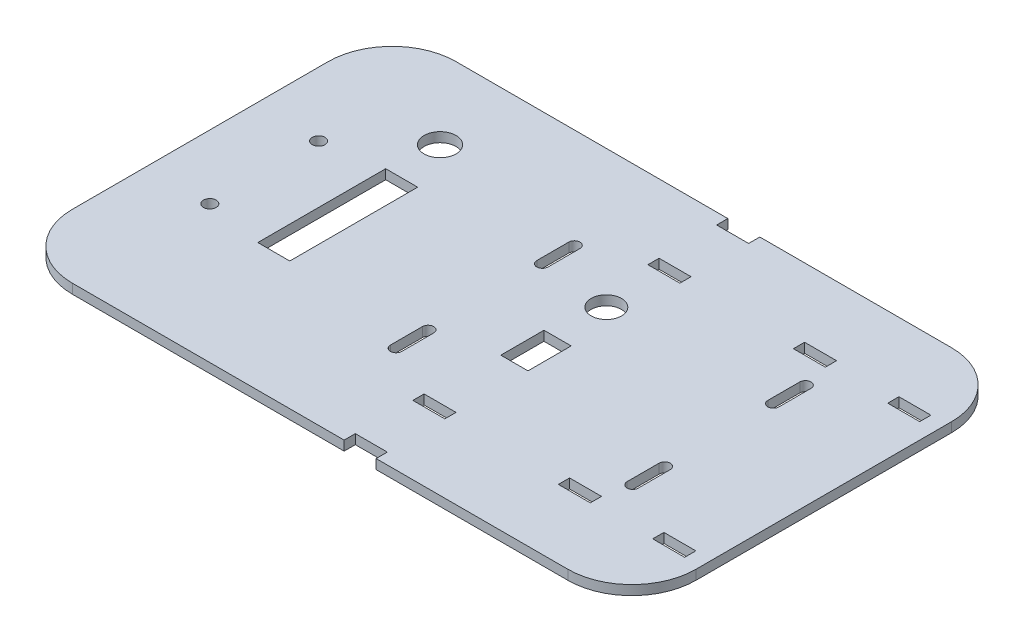
SolidWorks part; units mm, degrees
ref_plane "Plano frontal" through (0, 0, 0) normal (0, 0, 1) x (1, 0, 0)
ref_plane "Plano superior" through (0, 0, 0) normal (0, 1, 0) x (1, 0, 0)
ref_plane "Plano direito" through (0, 0, 0) normal (1, 0, 0) x (0, 0, -1)
sketch "Esboço1" plane through (0, 0, 0) normal (0, 1, 0) x (1, 0, 0)
  line L1 (0, 0) -> (195, 0)
  line L2 (0, 0) -> (0, 120)
  line L3 (0, 120) -> (195, 120)
  line L4 (195, 0) -> (195, 120)
  dimension "D1" = 195
  dimension "D2" = 120
extrude "Ressalto-extrusão1" add sketch "Esboço1" along normal blind 3
fillet "Filete1" radius 20 1 edges at (0, 1.5, 0)
fillet "Filete2" radius 20 1 edges at (195, 1.5, 0)
fillet "Filete3" radius 20 1 edges at (195, 1.5, -120)
fillet "Filete4" radius 20 1 edges at (0, 1.5, -120)
sketch "Esboço2" plane through (0, 3, 0) normal (0, 1, 0) x (1, 0, 0)
  line L0 (195, 20) -> (195, 100) construction
  line L1 (105, 3.5) -> (115, 3.5)
  line L2 (105, 3.5) -> (105, 0)
  line L3 (105, 0) -> (115, 0)
  line L4 (115, 3.5) -> (115, 0)
  line L5 (20, 0) -> (175, 0) construction
  line L6 (175, 120) -> (20, 120) construction
  line L7 (105, 120) -> (115, 120)
  line L8 (105, 120) -> (105, 116.5)
  line L9 (105, 116.5) -> (115, 116.5)
  line L10 (115, 120) -> (115, 116.5)
  line L11 (105, 25) -> (115, 25)
  line L12 (105, 98.5) -> (115, 98.5)
  line L13 (105, 98.5) -> (105, 95)
  line L14 (105, 95) -> (115, 95)
  line L15 (115, 98.5) -> (115, 95)
  line L16 (105, 25) -> (105, 21.5)
  line L17 (105, 21.5) -> (115, 21.5)
  line L18 (115, 25) -> (115, 21.5)
  line L19 (150.5, 25) -> (160.5, 25)
  line L20 (150.5, 25) -> (150.5, 21.5)
  line L21 (150.5, 21.5) -> (160.5, 21.5)
  line L22 (160.5, 25) -> (160.5, 21.5)
  line L23 (180, 25) -> (190, 25)
  line L24 (180, 25) -> (180, 21.5)
  line L25 (180, 21.5) -> (190, 21.5)
  line L26 (190, 25) -> (190, 21.5)
  line L27 (150.5, 98.5) -> (160.5, 98.5)
  line L28 (150.5, 98.5) -> (150.5, 95)
  line L29 (150.5, 95) -> (160.5, 95)
  line L30 (160.5, 98.5) -> (160.5, 95)
  line L31 (180, 98.5) -> (190, 98.5)
  line L32 (180, 98.5) -> (180, 95)
  line L33 (180, 95) -> (190, 95)
  line L34 (190, 98.5) -> (190, 95)
  point P38 (115, 23.25)
  point P39 (190, 23.25)
  dimension "D1" = 10
  dimension "D2" = 3.5
  dimension "D3" = 80
  dimension "D4" = 0
  dimension "D5" = 10
  dimension "D6" = 3.5
  dimension "D7" = 80
  dimension "D8" = 0
  dimension "D9" = 10
  dimension "D10" = 3.5
  dimension "D11" = 21.5
  dimension "D12" = 80
  dimension "D13" = 21.5
  dimension "D14" = 21.5
  dimension "D15" = 21.5
  dimension "D16" = 21.5
  dimension "D17" = 21.5
  dimension "D18" = 80
  dimension "D19" = 10
  dimension "D20" = 3.5
  dimension "D21" = 5
  dimension "D22" = 10
  dimension "D23" = 19.5
  dimension "D24" = 10
  dimension "D25" = 35.5
  dimension "D26" = 3.5
  dimension "D27" = 3.5
  dimension "D28" = 10
  dimension "D29" = 3.5
  dimension "D30" = 5
  dimension "D31" = 10
  dimension "D32" = 3.5
  dimension "D33" = 19.5
  dimension "D34" = 35.5
extrude "Corte-extrusão1" cut sketch "Esboço2" against normal through all
sketch "Esboço3" plane through (0, 3, 0) normal (0, 1, 0) x (1, 0, 0)
  line L0 (162.25, 87) -> (162.25, 77) construction
  line L1 (164, 87) -> (164, 77)
  line L2 (160.5, 87) -> (160.5, 77)
  line L3 (175, 120) -> (115, 120) construction
  line L4 (195, 20) -> (195, 100) construction
  line L5 (162.25, 43) -> (162.25, 33) construction
  line L6 (164, 43) -> (164, 33)
  line L7 (160.5, 43) -> (160.5, 33)
  line L8 (115, 0) -> (175, 0) construction
  line L9 (88.25, 43) -> (88.25, 33) construction
  line L10 (90, 43) -> (90, 33)
  line L11 (86.5, 43) -> (86.5, 33)
  line L12 (88.25, 88.75) -> (88.25, 78.75) construction
  line L13 (90, 88.75) -> (90, 78.75)
  line L14 (86.5, 88.75) -> (86.5, 78.75)
  line L15 (105, 120) -> (20, 120) construction
  line L16 (20, 0) -> (105, 0) construction
  arc A0 (164, 87) -> (160.5, 87) centre (162.25, 87) ccw
  arc A1 (160.5, 77) -> (164, 77) centre (162.25, 77) ccw
  arc A2 (164, 43) -> (160.5, 43) centre (162.25, 43) ccw
  arc A3 (160.5, 33) -> (164, 33) centre (162.25, 33) ccw
  arc A4 (90, 43) -> (86.5, 43) centre (88.25, 43) ccw
  arc A5 (86.5, 33) -> (90, 33) centre (88.25, 33) ccw
  arc A6 (90, 88.75) -> (86.5, 88.75) centre (88.25, 88.75) ccw
  arc A7 (86.5, 78.75) -> (90, 78.75) centre (88.25, 78.75) ccw
  point P2 (162.25, 82)
  point P13 (162.25, 38)
  point P24 (88.25, 38)
  point P31 (88.25, 83.75)
  point P38 (88.25, 77)
  dimension "D1" = 1.75
  dimension "D6" = 1.75
  dimension "D10" = 1.75
  dimension "D14" = 1.75
  dimension "D16" = 43
  dimension "D2" = 10
  dimension "D3" = 33
  dimension "D4" = 32.75
  dimension "D5" = 10
  dimension "D7" = 32.75
  dimension "D8" = 33
  dimension "D9" = 10
  dimension "D11" = 74
  dimension "D12" = 43
  dimension "D13" = 10
  dimension "D15" = 74
extrude "Corte-extrusão2" cut sketch "Esboço3" against normal through all
sketch "Esboço4" plane through (0, 3, 0) normal (0, 1, 0) x (1, 0, 0)
  line L0 (105, 120) -> (20, 120) construction
  line L1 (195, 20) -> (195, 100) construction
  line L2 (20, 0) -> (105, 0) construction
  line L3 (106.5, 61) -> (115, 61)
  line L4 (106.5, 61) -> (106.5, 47.5)
  line L5 (106.5, 47.5) -> (115, 47.5)
  line L6 (115, 61) -> (115, 47.5)
  circle A0 centre (110, 77) radius 4.75
  dimension "D1" = 9.5
  dimension "D2" = 43
  dimension "D3" = 85
  dimension "D4" = 8.5
  dimension "D5" = 13.5
  dimension "D6" = 47.5
  dimension "D7" = 80
extrude "Corte-extrusão3" cut sketch "Esboço4" against normal through all
sketch "Esboço5" plane through (0, 3, 0) normal (0, 1, 0) x (1, 0, 0)
  line L0 (105, 120) -> (20, 120) construction
  line L1 (0, 100) -> (0, 20) construction
  line L2 (20, 0) -> (105, 0) construction
  line L4 (38, 80) -> (48, 80)
  line L5 (38, 80) -> (38, 40)
  line L6 (38, 40) -> (48, 40)
  line L7 (48, 80) -> (48, 40)
  circle A0 centre (40, 95) radius 5
  circle A1 centre (20, 77) radius 2
  circle A2 centre (20, 43) radius 2
  dimension "D4" = 4
  dimension "D5" = 4
  dimension "D12" = 10
  dimension "D13" = 20
  dimension "D2" = 25
  dimension "D3" = 40
  dimension "D6" = 43
  dimension "D7" = 43
  dimension "D8" = 10
  dimension "D9" = 40
  dimension "D10" = 40
  dimension "D11" = 38
  dimension "D14" = 20
extrude "Corte-extrusão4" cut sketch "Esboço5" against normal through all
